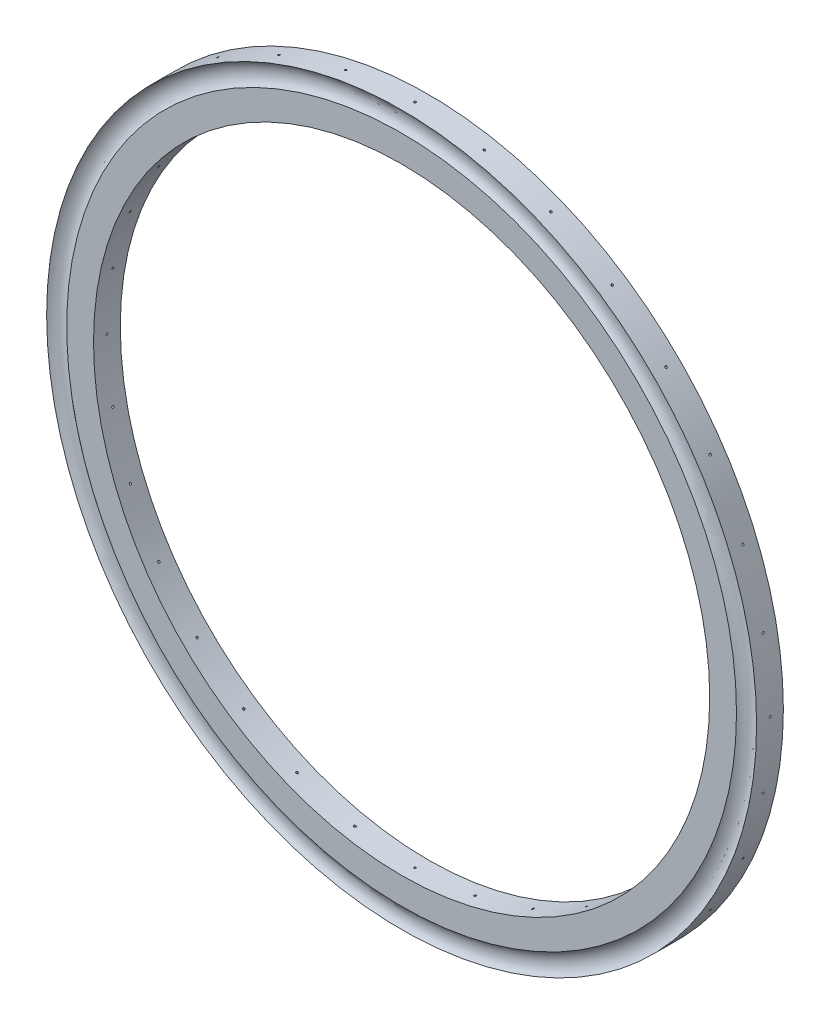
SolidWorks part; units mm, degrees
ref_plane "Front Plane" through (0, 0, 0) normal (0, 0, 1) x (1, 0, 0)
ref_plane "Top Plane" through (0, 0, 0) normal (0, 1, 0) x (1, 0, 0)
ref_plane "Right Plane" through (0, 0, 0) normal (1, 0, 0) x (0, 0, -1)
sketch "Sketch1" plane through (0, 0, 0) normal (0, 1, 0) x (1, 0, 0)
  line L0 (317.5, 12.7) -> (292.1, 12.7)
  line L1 (317.5, 12.7) -> (317.5, -12.7) construction
  line L2 (292.1, 12.7) -> (292.1, -12.7)
  line L3 (317.5, -12.7) -> (292.1, -12.7)
  line L4 (0, 0) -> (292.1, 0) construction
  line L5 (317.5, 12.7) -> (292.1, -12.7) construction
  line L6 (292.1, 12.7) -> (317.5, -12.7) construction
  line L7 (336.55, 12.7) -> (336.55, -12.7)
  line L8 (0, 0) -> (0, 148.9286) construction
  arc A0 (317.5, 12.7) -> (336.55, 12.7) centre (327.025, 23.1909) ccw
  arc A1 (317.5, -12.7) -> (336.55, -12.7) centre (327.025, -23.1909) cw
  point P1 (304.8, 0)
  dimension "D1" = 25.4
  dimension "D2" = 25.4
  dimension "D3" = 317.5
  dimension "D4" = 336.55
revolve "Revolve1" add sketch "Sketch1" angle 360 about L8
sketch "Sketch2" plane through (0, 0, 0) normal (1, 0, 0) x (0, 0, -1)
  circle A0 centre (0, 0) radius 1
  dimension "D1" = 2
extrude "Cut-Extrude1" cut sketch "Sketch2" against normal through all
pattern_circular "CirPattern1" count 32 over 360 of "Cut-Extrude1"
